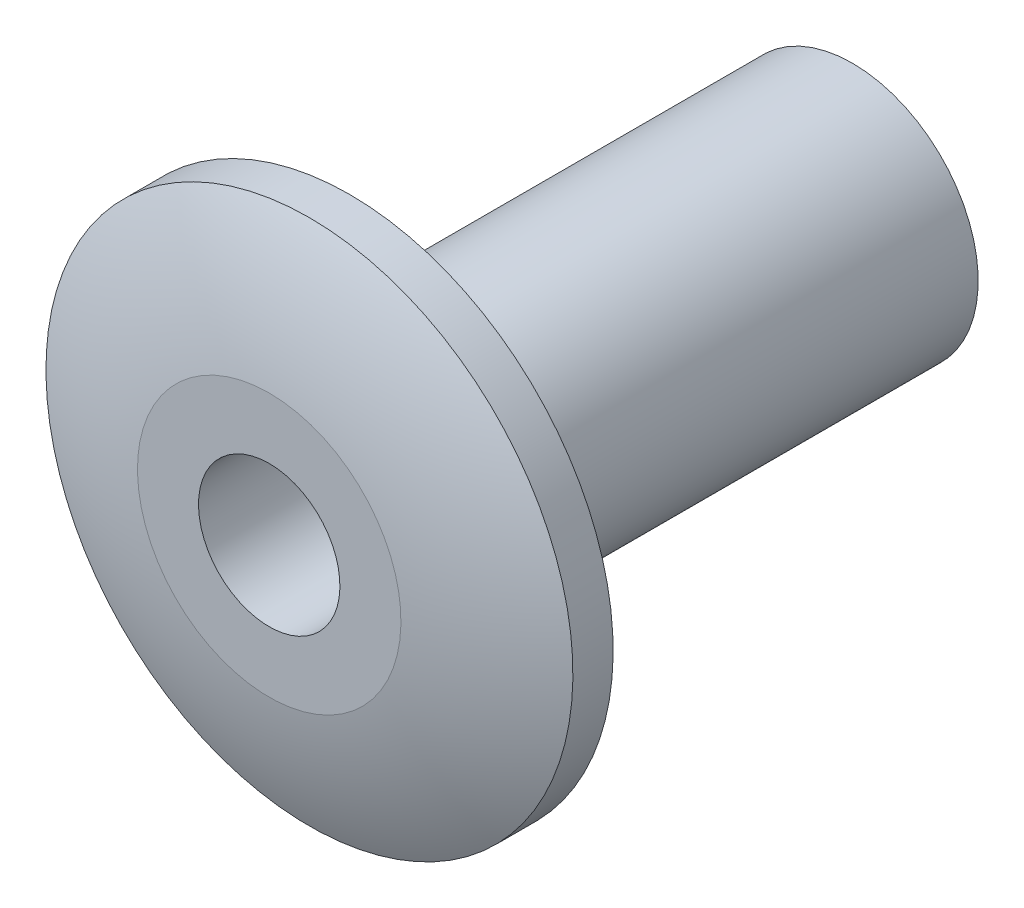
SolidWorks part; units mm, degrees
ref_plane "Front" through (0, 0, 0) normal (0, 0, 1) x (1, 0, 0)
ref_plane "Top" through (0, 0, 0) normal (0, 1, 0) x (1, 0, 0)
ref_plane "Right" through (0, 0, 0) normal (1, 0, 0) x (0, 0, -1)
sketch "Sketch1" plane through (0, 0, 0) normal (1, 0, 0) x (0, 0, -1)
  line L0 (-10.541, 0) -> (-1.016, 0) construction
  line L1 (-1.016, 0) -> (0, 0) construction
  line L2 (0, 0) -> (6.35, 0) construction
  line L3 (6.35, 0) -> (7.874, 0) construction
  line L8 (0, 3.3274) -> (0, -3.3274) construction
  line L9 (6.35, 1.5875) -> (6.35, -1.5875) construction
  dimension "Length" = 6.35
  dimension "Head Height" = 1.016
  dimension "D5" = 1.524
  dimension "D9" = 9.525
  dimension "Diameter" = 3.175
  dimension "Head Diameter" = 6.6548
sketch "Sketch2" plane through (0, 0, 0) normal (1, 0, 0) x (0, 0, -1)
  line L0 (-10.541, 0.7937) -> (-10.541, 0) construction
  line L1 (-10.541, 0.7937) -> (0, 0.7937) construction
  line L2 (0, 3.3274) -> (0, -3.3274) construction
  line L3 (0, 0) -> (0, 3.3274) construction
  line L4 (-1.016, 0) -> (-1.016, -1.8472) construction
  line L5 (6.35, 1.5875) -> (0, 1.5875)
  line L6 (6.35, 1.5875) -> (6.35, 0) construction
  line L7 (7.874, 0) -> (7.874, 1.5875) construction
  line L8 (6.35, 1.5875) -> (6.35, 0)
  line L9 (7.874, 1.5875) -> (6.35, 1.5875) construction
  line L10 (-1.016, 0.893) -> (-1.016, 1.6637)
  line L11 (6.35, 0) -> (7.874, 0) construction
  line L12 (6.35, 0) -> (0.635, 0)
  line L13 (-1.016, 0.7937) -> (-1.016, 0) construction
  line L14 (6.35, 1.5875) -> (6.35, 0) construction
  line L15 (6.35, 1.5875) -> (6.35, 0) construction
  line L16 (6.35, 0) -> (6.35, 1.5875) construction
  line L17 (6.35, 1.5875) -> (6.35, 0) construction
  line L18 (6.35, 0) -> (6.35, 1.5875) construction
  line L19 (0, 1.5875) -> (0, 3.3274)
  line L20 (-1.016, 0.893) -> (0, 0.893)
  line L21 (-10.541, 0.893) -> (0, 0.893) construction
  line L22 (0, 3.3274) -> (-0.508, 3.3274)
  line L23 (0, 0.893) -> (0.635, 0.893)
  line L24 (0.635, 0.893) -> (0.635, 0)
  arc A0 (7.874, 0) -> (6.35, 1.27) centre (6.5828, 0) ccw construction
  arc A2 (-0.508, 3.3274) -> (-1.016, 1.6637) centre (4.8114, 0.7937) ccw
  dimension "D3" = 0.508
  dimension "D1" = 0.7937
  dimension "D2" = 0.635
  dimension "D5" = 1.27
  dimension "D6" = 1.6637
  dimension "D4" = 0.0992
revolve "Revolve1" add sketch "Sketch2" angle 360 about L12
sketch "Sketch7" plane through (0, 0, 0) normal (1, 0, 0) x (0, 0, -1)
  line L0 (-9.788, 0.7937) -> (0.635, 0.7937)
  line L1 (0.635, 0.893) -> (0.635, 0) construction
  line L2 (0.635, 0.7937) -> (0.635, 0)
  line L3 (0.635, 0) -> (-10.541, 0)
  line L5 (-10.417, 0.266) -> (-9.788, 0.7937)
  arc A0 (-10.541, 0) -> (-10.417, 0.266) centre (-10.1937, 0) cw
  dimension "D1" = 0.3473
  dimension "D2" = 40
revolve "Revolve2" [suppressed] add sketch "Sketch7" angle 360 about L0
sketch "Sketch8" plane through (0, 0, 0) normal (1, 0, 0) x (0, 0, -1)
  line L1 (6.35, 1.27) -> (6.35, 0)
  line L2 (6.35, 0) -> (7.874, 0) construction
  line L3 (7.874, 0) -> (6.5828, 0) construction
  line L4 (7.5512, 0) -> (6.35, 0)
  line L5 (6.35, 1.27) -> (6.6992, 1.27) construction
  arc A0 (7.874, 0) -> (6.35, 1.27) centre (6.5828, 0) ccw construction
  arc A1 (6.6993, 1.2859) -> (6.35, 1.27) centre (6.5828, 0) ccw
  arc A2 (6.6993, 1.2859) -> (7.5512, 0) centre (6.1548, 0) cw
  circle A3 centre (6.5828, 0) radius 1.2912 construction
  point P7 (7.5512, 0)
  point P8 (7.2284, 0)
  point P9 (6.9056, 0)
  point P12 (6.4664, 1.27)
  point P13 (6.5828, 1.27)
revolve "Revolve3" [suppressed] add sketch "Sketch8" angle 360 about L3
sketch "Sketch3" [suppressed] plane through (0, 0, 0) normal (0, 1, 0) x (1, 0, 0)
  line L0 (-0.997, -8.4087) -> (-0.2209, -10.541)
  line L1 (-0.2209, -10.541) -> (0.2209, -10.541)
  line L3 (0, -10.541) -> (0, -11.049) construction
  line L4 (0.266, -10.417) -> (-0.266, -10.417) construction
  line L5 (-0.997, -8.4087) -> (-0.997, -11.049)
  line L6 (-0.997, -11.049) -> (0.9969, -11.049)
  line L7 (0.9969, -11.049) -> (0.9969, -8.4087)
  line L8 (-0.7937, 0.635) -> (-0.7937, -9.788) construction
  line L9 (0, -10.541) -> (0, -1.016) construction
  line L10 (0.2209, -10.541) -> (0.9969, -8.4087)
  line L11 (-0.7937, -9.788) -> (-0.266, -10.417) construction
  arc A0 (-0.266, -10.417) -> (0.266, -10.417) centre (0, -10.1937) ccw construction
  point P11 (-0.266, -10.417)
  point P25 (0, -10.541)
  dimension "D1" = 40
  dimension "D2" = 0.2032
  dimension "D3" = 0.508
extrude "Cut-Extrude1" [suppressed] cut sketch "Sketch3" against normal through all both and the other way through all
pattern_circular "CirPattern1" [suppressed] count 2 every 90 about axis through (0, 0, 10.541) along (0, 0, -1)
sketch "Sketch9" [suppressed] plane through (0, 0, 0) normal (0, 1, 0) x (1, 0, 0)
  line L0 (0, -10.541) -> (0, 19.9517) construction
  line L1 (0, 6.35) -> (0, 7.874) construction
  line L2 (3.3274, 0) -> (-3.3274, 0) construction
  line L3 (2.0356, 0) -> (2.1341, 0)
  line L4 (2.0356, 0) -> (2.0356, 0.0254)
  line L5 (2.0356, 0.0254) -> (2.1341, 0.0254)
  line L6 (2.1341, 0) -> (2.1341, 0.0254)
  line L8 (2.3081, 0) -> (2.4066, 0)
  line L9 (2.3081, 0) -> (2.3081, 0.0254)
  line L10 (2.3081, 0.0254) -> (2.4066, 0.0254)
  line L11 (2.4066, 0) -> (2.4066, 0.0254)
  line L12 (2.551, 0) -> (2.6495, 0)
  line L13 (2.551, 0) -> (2.551, 0.0254)
  line L14 (2.551, 0.0254) -> (2.6495, 0.0254)
  line L15 (2.6495, 0) -> (2.6495, 0.0254)
  line L16 (2.9023, 0) -> (3.0008, 0)
  line L17 (2.9023, 0) -> (2.9023, 0.0254)
  line L18 (2.9023, 0.0254) -> (3.0008, 0.0254)
  line L19 (3.0008, 0) -> (3.0008, 0.0254)
  line L20 (1.9076, 0) -> (1.8091, 0)
  line L21 (1.9076, 0) -> (1.9076, 0.0254)
  line L22 (1.9076, 0.0254) -> (1.8091, 0.0254)
  line L23 (1.8091, 0) -> (1.8091, 0.0254)
  point P24 (2.9515, 0.0254)
  point P25 (2.6003, 0.0254)
  point P26 (2.3573, 0.0254)
  point P27 (2.0848, 0.0254)
  point P32 (1.8583, 0.0254)
  dimension "D1" = 0.0985
  dimension "D2" = 0.0254
  dimension "D3" = 5.903
  dimension "D4" = 5.2005
  dimension "D5" = 4.7146
  dimension "D6" = 4.1697
  dimension "D7" = 3.7167
revolve "Revolve4" [suppressed] add sketch "Sketch9" angle 360 about L0
equation "\"D5@Sketch1\" = \"Head Height@Sketch1\" * 1.5"
equation "\"D9@Sketch1\" = \"Length@Sketch1\" * 1.5"
equation "\"D1@Sketch2\"=\"Diameter@Sketch1\"/4"
equation "\"D4@Sketch2\"=\"D1@Sketch2\"/8"
equation "\"D2@Sketch2\"=\"Length@Sketch1\"/10"
equation "\"D5@Sketch2\"=\"Diameter@Sketch1\"*.8/2"
equation "\"D1@Sketch7\"=(\"D1@Sketch2\"-\"D4@Sketch2\")*2*.25"
equation "\"D6@Sketch2\"=\"Head Diameter@Sketch1\"/2*.5"
equation "\"D7@Sketch9\"=.15566*(\"Head Diameter@Sketch1\"-\"Diameter@Sketch1\")+\"Diameter@Sketch1\""
equation "\"D3@Sketch9\"=.7839623*(\"Head Diameter@Sketch1\"-\"Diameter@Sketch1\")+\"Diameter@Sketch1\""
equation "\"D1@Sketch9\"=.028302*(\"Head Diameter@Sketch1\"-\"Diameter@Sketch1\")"
equation "\"D6@Sketch9\"=.285849*(\"Head Diameter@Sketch1\"-\"Diameter@Sketch1\")+\"Diameter@Sketch1\""
equation "\"D5@Sketch9\"=.4424528*(\"Head Diameter@Sketch1\"-\"Diameter@Sketch1\")+\"Diameter@Sketch1\""
equation "\"D4@Sketch9\"=.582075*(\"Head Diameter@Sketch1\"-\"Diameter@Sketch1\")+\"Diameter@Sketch1\""
